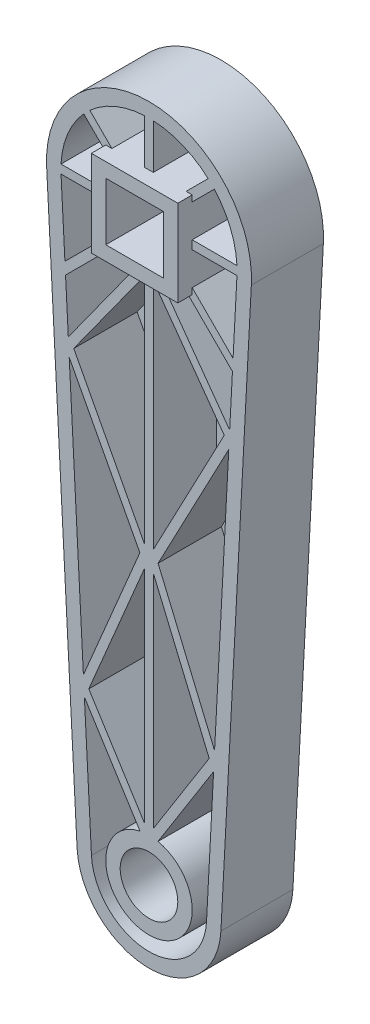
SolidWorks part; units mm, degrees
ref_plane "Front Plane" through (0, 0, 0) normal (0, 0, 1) x (1, 0, 0)
ref_plane "Top Plane" through (0, 0, 0) normal (0, 1, 0) x (1, 0, 0)
ref_plane "Right Plane" through (0, 0, 0) normal (1, 0, 0) x (0, 0, -1)
sketch "Sketch1" plane through (0, 0, 0) normal (0, 0, 1) x (1, 0, 0)
  line L0 (0, 0) -> (0, -200) construction
  line L1 (-10, 10) -> (10, 10)
  line L2 (-10, 10) -> (-10, -10)
  line L3 (-10, -10) -> (10, -10)
  line L4 (10, 10) -> (10, -10)
  line L5 (-10, 10) -> (10, -10) construction
  line L6 (-10, -10) -> (10, 10) construction
  line L7 (-35.5252, -1.881) -> (-24.965, -201.3219)
  line L8 (24.965, -201.3219) -> (35.5252, -1.881)
  circle A0 centre (0, -200) radius 10
  circle A1 centre (0, -200) radius 25 construction
  circle A2 centre (0, 0) radius 35.575 construction
  arc A3 (-35.5252, -1.881) -> (35.5252, -1.881) centre (0, 0) cw
  arc A4 (-24.965, -201.3219) -> (24.965, -201.3219) centre (0, -200) ccw
  point P0 (0, 0)
  point P15 (24.9444, -201.6669)
  dimension "D3" = 20
  dimension "D4" = 15
  dimension "D5" = 71.15
  dimension "D1" = 20
  dimension "D2" = 200
extrude "Boss-Extrude1" add sketch "Sketch1" along normal blind 25
sketch "Sketch2" plane through (0, 0, 25) normal (0, 0, 1) x (1, 0, 0)
  line L4 (-30.5322, -1.6167) -> (-19.972, -201.0575)
  line L5 (19.972, -201.0575) -> (30.5322, -1.6167)
  line L6 (-30.5322, -1.6167) -> (-19.972, -201.0575)
  line L7 (19.972, -201.0575) -> (30.5322, -1.6167)
  line L26 (15, -15) -> (15, 15)
  line L27 (-15, -15) -> (15, -15)
  line L28 (-15, 15) -> (-15, -15)
  line L29 (15, 15) -> (-15, 15)
  line L30 (15, -15) -> (15, 15)
  line L31 (-15, -15) -> (15, -15)
  line L32 (-15, 15) -> (-15, -15)
  line L33 (15, 15) -> (-15, 15)
  arc A4 (30.5322, -1.6167) -> (-30.5322, -1.6167) centre (0, 0) ccw
  arc A5 (-19.972, -201.0575) -> (19.972, -201.0575) centre (0, -200) ccw
  arc A6 (30.5322, -1.6167) -> (-30.5322, -1.6167) centre (0, 0) ccw
  arc A7 (-19.972, -201.0575) -> (19.972, -201.0575) centre (0, -200) ccw
  circle A11 centre (0, -200) radius 15
  circle A12 centre (0, -200) radius 15
  dimension "D1" = 5
  dimension "D2" = 5
  dimension "D3" = 5
extrude "Cut-Extrude1" cut sketch "Sketch2" against normal offset from surface (22 mm away) 3 up to face at (0, 0, 0)
sketch "Sketch3" plane through (0, 0, 25) normal (0, 0, 1) x (1, 0, 0)
  line L0 (-10, 10) -> (-21.6198, 21.6198) construction
  line L1 (10, 10) -> (21.6198, 21.6198) construction
  line L2 (19.972, -201.0575) -> (30.5322, -1.6167) construction
  line L4 (-30.5322, -1.6167) -> (-19.972, -201.0575) construction
  line L6 (-10, 0) -> (-30.575, 0) construction
  line L8 (10, 0) -> (30.575, 0) construction
  line L9 (10, -10) -> (10, 10) construction
  line L10 (0, 10) -> (0, 30.575) construction
  line L11 (10, 10) -> (-10, 10) construction
  line L12 (0, -10) -> (0, -190) construction
  line L13 (-10, -10) -> (10, -10) construction
  line L14 (-10, 10) -> (-10, -10) construction
  line L19 (-8.9393, 11.0607) -> (-20.5591, 22.6805)
  line L20 (-30.575, 1.5) -> (-10, 1.5)
  line L21 (-1.5, 30.575) -> (1.5, 30.575)
  line L22 (-1.5, 30.575) -> (-1.5, 10)
  line L23 (-1.5, 10) -> (1.5, 10)
  line L24 (1.5, 30.575) -> (1.5, 10)
  line L25 (-1.5, 30.575) -> (1.5, 10) construction
  line L26 (-1.5, 10) -> (1.5, 30.575) construction
  line L27 (30.575, -1.5) -> (10, -1.5)
  line L28 (30.575, -1.5) -> (30.575, 1.5)
  line L29 (30.575, 1.5) -> (10, 1.5)
  line L30 (10, -1.5) -> (10, 1.5)
  line L31 (30.575, -1.5) -> (10, 1.5) construction
  line L32 (30.575, 1.5) -> (10, -1.5) construction
  line L33 (-30.575, 1.5) -> (-30.575, -1.5)
  line L34 (-30.575, -1.5) -> (-10, -1.5)
  line L35 (-10, 1.5) -> (-10, -1.5)
  line L36 (-30.575, 1.5) -> (-10, -1.5) construction
  line L37 (-30.575, -1.5) -> (-10, 1.5) construction
  line L38 (-1.5, -190) -> (1.5, -190)
  line L39 (-1.5, -190) -> (-1.5, -10)
  line L40 (-1.5, -10) -> (1.5, -10)
  line L41 (1.5, -190) -> (1.5, -10)
  line L42 (-1.5, -190) -> (1.5, -10) construction
  line L43 (-1.5, -10) -> (1.5, -190) construction
  line L44 (11.0607, 8.9393) -> (22.6805, 20.5591)
  line L45 (8.9393, -11.0607) -> (28.9715, -31.0928)
  line L46 (-11.0607, -8.9393) -> (-31.0928, -28.9715)
  line L47 (-11.0607, 8.9393) -> (-22.6805, 20.5591)
  line L48 (8.9393, 11.0607) -> (20.5591, 22.6805)
  line L49 (11.0607, -8.9393) -> (31.0928, -28.9715)
  line L50 (-8.9393, -11.0607) -> (-28.9715, -31.0928)
  line L51 (-8.9393, 11.0607) -> (-11.0607, 8.9393)
  line L52 (-20.5591, 22.6805) -> (-22.6805, 20.5591)
  line L53 (11.0607, 8.9393) -> (8.9393, 11.0607)
  line L54 (22.6805, 20.5591) -> (20.5591, 22.6805)
  line L55 (8.9393, -11.0607) -> (11.0607, -8.9393)
  line L56 (28.9715, -31.0928) -> (31.0928, -28.9715)
  line L57 (-11.0607, -8.9393) -> (-8.9393, -11.0607)
  line L58 (-31.0928, -28.9715) -> (-28.9715, -31.0928)
  arc A0 (30.5322, -1.6167) -> (-30.5322, -1.6167) centre (0, 0) ccw construction
  arc A1 (30.5322, -1.6167) -> (-30.5322, -1.6167) centre (0, 0) ccw construction
  circle A3 centre (0, -200) radius 10 construction
  point P12 (27.6288, -30.7144)
  point P13 (29.508, -32.9913)
  point P14 (30.0508, -10.7083)
  point P17 (0, 0)
  point P19 (28.809, -34.1619)
  point P21 (-31.0886, -28.0198)
  point P23 (31.0573, -28.9715)
  point P24 (0, 0)
  point P30 (-20.2875, 0)
  point P33 (-10, -10)
  point P52 (0, -100)
  point P55 (0, 20.2875)
  point P60 (20.2875, 0)
  point P67 (-21.6198, 21.6198)
  point P68 (-10, 10)
  point P69 (-21.6198, 21.6198)
  point P86 (-28.0175, -30.1388)
  point P87 (-11.0607, -8.9393)
  point P88 (-29.0782, -29.0782)
  point P89 (-29.0004, -30.5462)
  point P91 (-28.0175, -30.1388)
  point P92 (-11.0607, -8.9393)
  dimension "D1" = 3
  dimension "D2" = 1.5
  dimension "D3" = 1.5
extrude "Boss-Extrude3" add sketch "Sketch3" against normal up to surface (22 mm away) up to face at (0, -98.0248, 3)
sketch "Sketch6" plane through (0, 0, 25) normal (0, 0, 1) x (1, 0, 0)
  line L0 (-32.8926, -51.6015) -> (32.8926, -51.6015) construction
  line L1 (-35.5252, -1.881) -> (-24.965, -201.3219) construction
  line L2 (24.965, -201.3219) -> (35.5252, -1.881) construction
  line L3 (30.2451, -101.6015) -> (-30.2451, -101.6015) construction
  line L4 (27.5977, -151.6015) -> (-27.5977, -151.6015) construction
  line L5 (-1.5, -15) -> (-27.8856, -51.6015) construction
  line L6 (-28.9715, -31.0928) -> (-19.972, -201.0575) construction
  line L7 (-27.8856, -51.6015) -> (-1.5, -101.6015) construction
  line L8 (-1.5, -15) -> (-1.5, -185.0752) construction
  line L9 (-1.5, -101.6015) -> (-22.5907, -151.6015) construction
  line L10 (-28.9715, -31.0928) -> (-19.972, -201.0575) construction
  line L11 (-22.5907, -151.6015) -> (-1.5, -185.0752) construction
  line L12 (-1.5, -185.0752) -> (1.5, -185.0752) construction
  line L13 (1.5, -185.0752) -> (22.5907, -151.6015) construction
  line L14 (19.972, -201.0575) -> (28.9715, -31.0928) construction
  line L15 (22.5907, -151.6015) -> (1.5, -101.6015) construction
  line L16 (1.5, -15) -> (1.5, -185.0752) construction
  line L17 (1.5, -101.6015) -> (27.8856, -51.6015) construction
  line L18 (27.8856, -51.6015) -> (1.5, -15) construction
  line L19 (-2.7168, -14.1228) -> (-29.6463, -51.4788)
  line L20 (-29.6463, -51.4788) -> (-3.1582, -101.6731)
  line L21 (-3.1582, -101.6731) -> (-24.2768, -151.7392)
  line L22 (-24.2768, -151.7392) -> (-2.7691, -185.8748)
  line L23 (2.7691, -185.8748) -> (24.2768, -151.7392)
  line L24 (24.2768, -151.7392) -> (3.1582, -101.6731)
  line L25 (3.1582, -101.6731) -> (29.6463, -51.4788)
  line L26 (29.6463, -51.4788) -> (2.7168, -14.1228)
  line L27 (-0.2832, -15.8772) -> (-26.1248, -51.7241)
  line L28 (-26.1248, -51.7241) -> (0.1582, -101.5298)
  line L29 (0.1582, -101.5298) -> (-20.9046, -151.4637)
  line L30 (-20.9046, -151.4637) -> (-0.2309, -184.2756)
  line L31 (0.2309, -184.2756) -> (20.9046, -151.4637)
  line L32 (20.9046, -151.4637) -> (-0.1582, -101.5298)
  line L33 (-0.1582, -101.5298) -> (26.1248, -51.7241)
  line L34 (26.1248, -51.7241) -> (0.2832, -15.8772)
  line L35 (-2.7168, -14.1228) -> (-0.2832, -15.8772)
  line L36 (-2.7691, -185.8748) -> (-0.2309, -184.2756)
  line L37 (2.7691, -185.8748) -> (0.2309, -184.2756)
  line L38 (2.7168, -14.1228) -> (0.2832, -15.8772)
  line M13 (-12.8787, -15) -> (-1.5, -15)
  line M14 (-1.5, -15) -> (-1.5, -185.0752)
  arc M15 (-1.5, -185.0752) -> (1.5, -185.0752) centre (0, -200) ccw
  line M16 (1.5, -185.0752) -> (1.5, -15)
  line M17 (1.5, -15) -> (12.8787, -15)
  line M19 (28.9715, -31.0928) -> (19.972, -201.0575)
  line M21 (-19.972, -201.0575) -> (-28.9715, -31.0928)
  dimension "D1" = 50
  dimension "D2" = 50
  dimension "D3" = 1.5
  dimension "D4" = 1.5
extrude "Boss-Extrude4" add sketch "Sketch6" against normal up to surface (22 mm away) contours L34 L33 L32 L31 L23 L24 L25 L26 M16 M15 M19 M17 | L30 L29 L28 L27 L19 L20 L21 L22 M14 M13 M21 M15 up to face at (0, -94.3318, 3)
sketch "Sketch7" plane through (0, 0, 25) normal (0, 0, 1) x (1, 0, 0)
  line L0 (-10, 10) -> (-10, -10) construction
  line L1 (-10, -10) -> (10, -10) construction
  line L2 (10, -10) -> (10, 10) construction
  line L3 (10, 10) -> (-10, 10) construction
  line L4 (-10, 10) -> (-10, -10)
  line L5 (-10, -10) -> (10, -10)
  line L6 (10, -10) -> (10, 10)
  line L7 (10, 10) -> (-10, 10)
  line L9 (15, -15) -> (-15, -15)
  line L10 (15, -15) -> (15, 15)
  line L11 (15, 15) -> (-15, 15)
  line L12 (-15, -15) -> (-15, 15)
  line L13 (15, -15) -> (-15, 15) construction
  line L14 (15, 15) -> (-15, -15) construction
  line L15 (-15, 12.8787) -> (-15, 1.5) construction
  line L16 (-1.5, 15) -> (-12.8787, 15) construction
  point P2 (0, 0)
extrude "Boss-Extrude5" add sketch "Sketch7" along normal blind 5
